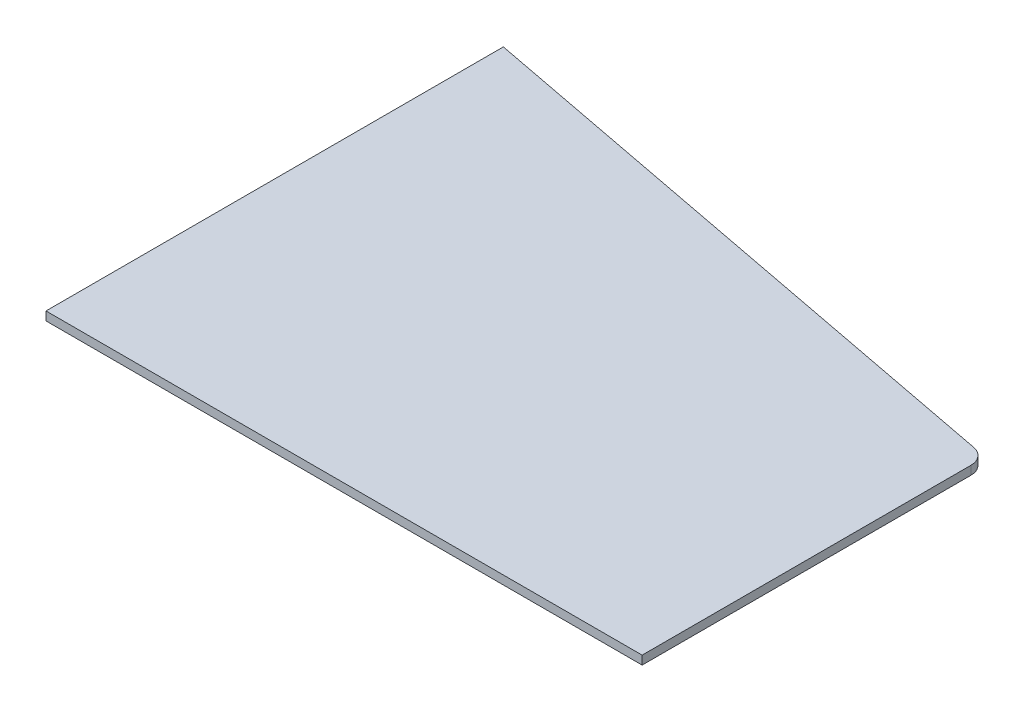
SolidWorks part; units mm, degrees
material "Balsa"
ref_plane "Front Plane" through (0, 0, 0) normal (0, 0, 1) x (1, 0, 0)
ref_plane "Top Plane" through (0, 0, 0) normal (0, 1, 0) x (1, 0, 0)
ref_plane "Right Plane" through (0, 0, 0) normal (1, 0, 0) x (0, 0, -1)
sketch "Sketch1" plane through (0, 0, 0) normal (0, 1, 0) x (1, 0, 0)
  line L0 (0, 0) -> (437.0222, 0)
  line L1 (426.7145, 253.437) -> (0, 335.28)
  line L2 (0, 335.28) -> (0, 0)
  line L3 (437.0222, 0) -> (437.0222, 240.9644)
  arc A0 (426.7145, 253.437) -> (437.0222, 240.9644) centre (424.3222, 240.9644) cw
  point P7 (437.0222, 251.46)
  dimension "D4" = 12.7
  dimension "D1" = 335.28
  dimension "D2" = 437.0222
  dimension "D3" = 251.46
extrude "Boss-Extrude1" add sketch "Sketch1" along normal blind 6.35
